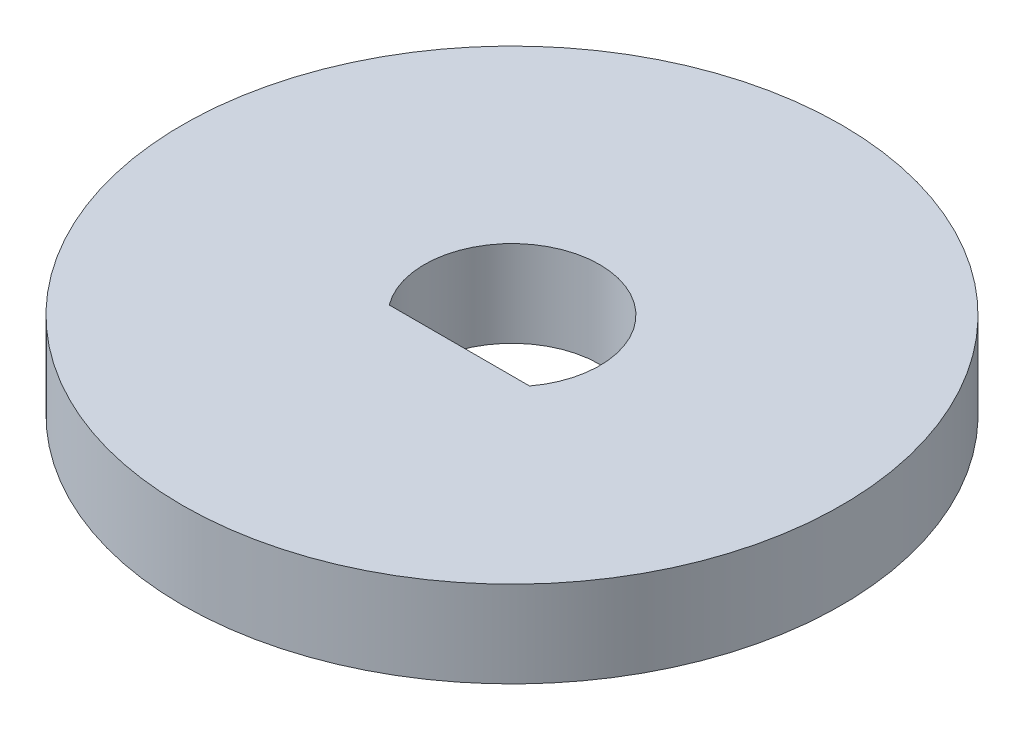
SolidWorks part; units mm, degrees
ref_plane "Front Plane" through (0, 0, 0) normal (0, 0, 1) x (1, 0, 0)
ref_plane "Top Plane" through (0, 0, 0) normal (0, 1, 0) x (1, 0, 0)
ref_plane "Right Plane" through (0, 0, 0) normal (1, 0, 0) x (0, 0, -1)
sketch "Sketch1" plane through (0, 0, 0) normal (0, 1, 0) x (1, 0, 0)
  circle A0 centre (0, 0) radius 9.398
  dimension "D1" = 18.796
extrude "Boss-Extrude1" add sketch "Sketch1" along normal blind 2.4638
sketch "Sketch2" plane through (0, 2.4638, 0) normal (0, 1, 0) x (1, 0, 0)
  line L0 (-2, -1.5) -> (2, -1.5)
  arc A0 (-2, -1.5) -> (2, -1.5) centre (0, 0) cw
  dimension "D1" = 2.5
  dimension "D2" = 1.5
extrude "Cut-Extrude1" cut sketch "Sketch2" against normal through all
